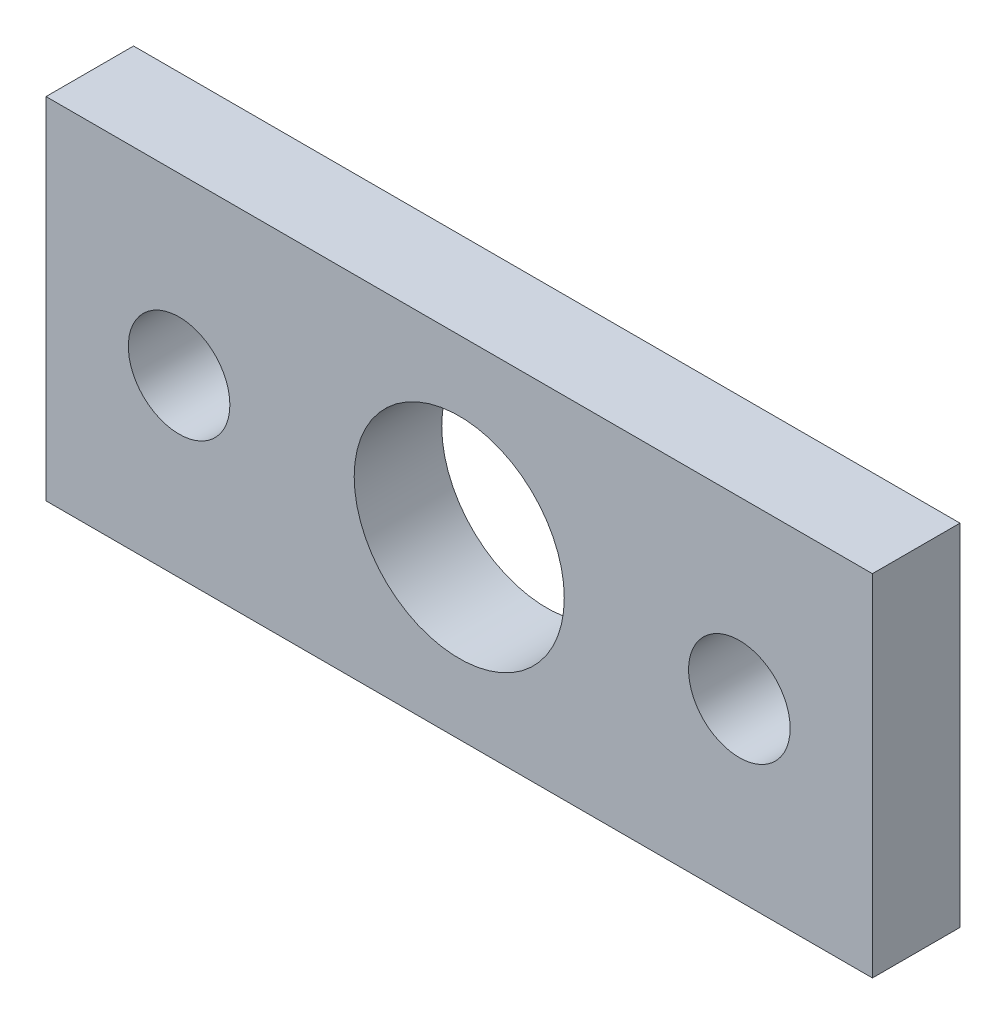
SolidWorks part; units mm, degrees
ref_plane "前视基准面" through (0, 0, 0) normal (0, 0, 1) x (1, 0, 0)
ref_plane "上视基准面" through (0, 0, 0) normal (0, 1, 0) x (1, 0, 0)
ref_plane "右视基准面" through (0, 0, 0) normal (1, 0, 0) x (0, 0, -1)
other "Configuration Table"
sketch "草图1" plane through (0, 0, 0) normal (0, 0, 1) x (1, 0, 0)
  line L0 (-11.8, -5) -> (11.8, -5)
  line L1 (11.8, -5) -> (11.8, 5)
  line L2 (11.8, 5) -> (-11.8, 5)
  line L3 (-11.8, 5) -> (-11.8, -5)
  circle A0 centre (-8, 0) radius 1.45
  circle A1 centre (8, 0) radius 1.45
  circle A2 centre (0, 0) radius 3
extrude "Plate_23.6x10_T2.5_M2.5_D2.9_P16" add sketch "草图1" along normal blind 2.5
sketch "草图2" plane through (0, 0, 0) normal (0, 0, 1) x (1, 0, 0)
  circle A0 centre (-8, 0) radius 2.8
  circle A1 centre (-8, 0) radius 1.45
  circle A2 centre (8, 0) radius 2.8
  circle A3 centre (8, 0) radius 1.45
extrude "Unit_recess_rings_OD5.6_ID2.9_H1" add sketch "草图2" against normal blind 1
